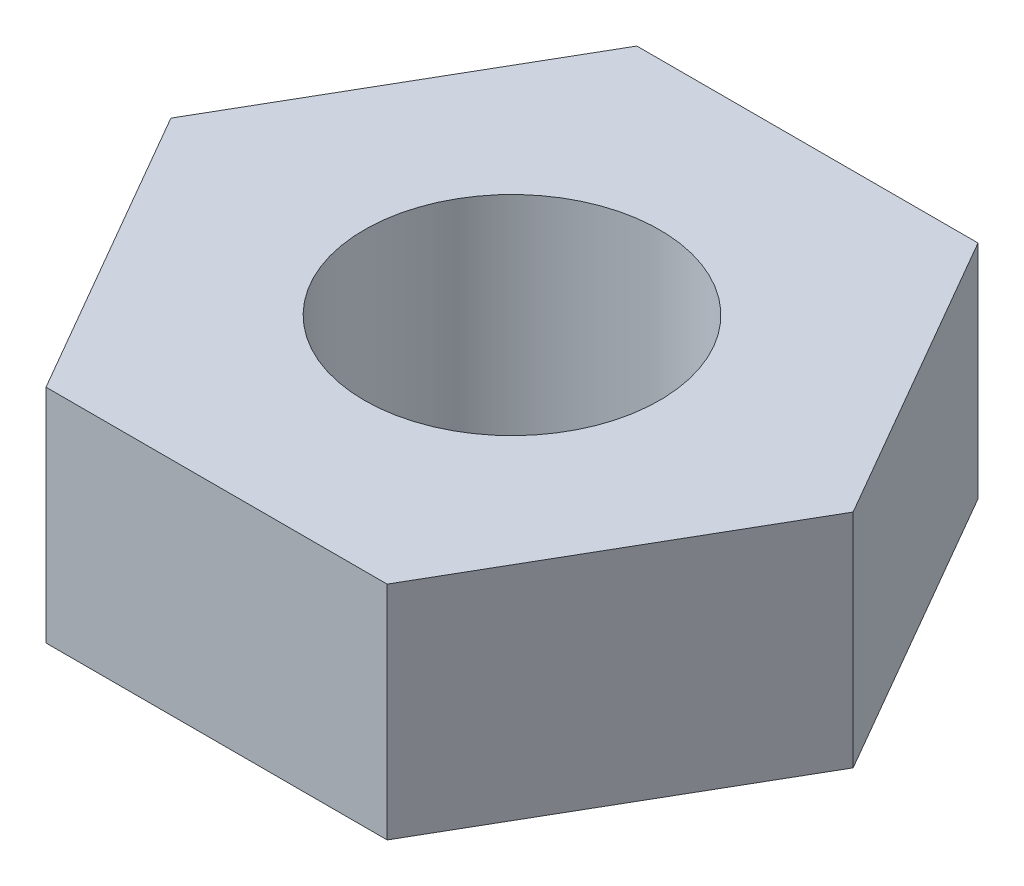
SolidWorks part; units mm, degrees
material "AISI 347 Annealed Stainless Steel (SS)"
ref_plane "Front Plane" through (0, 0, 0) normal (0, 0, 1) x (1, 0, 0)
ref_plane "Top Plane" through (0, 0, 0) normal (0, 1, 0) x (1, 0, 0)
ref_plane "Right Plane" through (0, 0, 0) normal (1, 0, 0) x (0, 0, -1)
sketch "Sketch1" plane through (0, 0, 0) normal (0, 1, 0) x (1, 0, 0)
  line L1 (2.3094, 0) -> (1.1547, 2)
  line L2 (1.1547, 2) -> (-1.1547, 2)
  line L3 (-1.1547, 2) -> (-2.3094, 0)
  line L4 (-2.3094, 0) -> (-1.1547, -2)
  line L5 (-1.1547, -2) -> (1.1547, -2)
  line L6 (1.1547, -2) -> (2.3094, 0)
  circle A0 centre (0, 0) radius 2 construction
  circle A1 centre (0, 0) radius 1
  dimension "D1" = 2
  dimension "D2" = 4
extrude "Boss-Extrude1" add sketch "Sketch1" along normal blind 1.5
